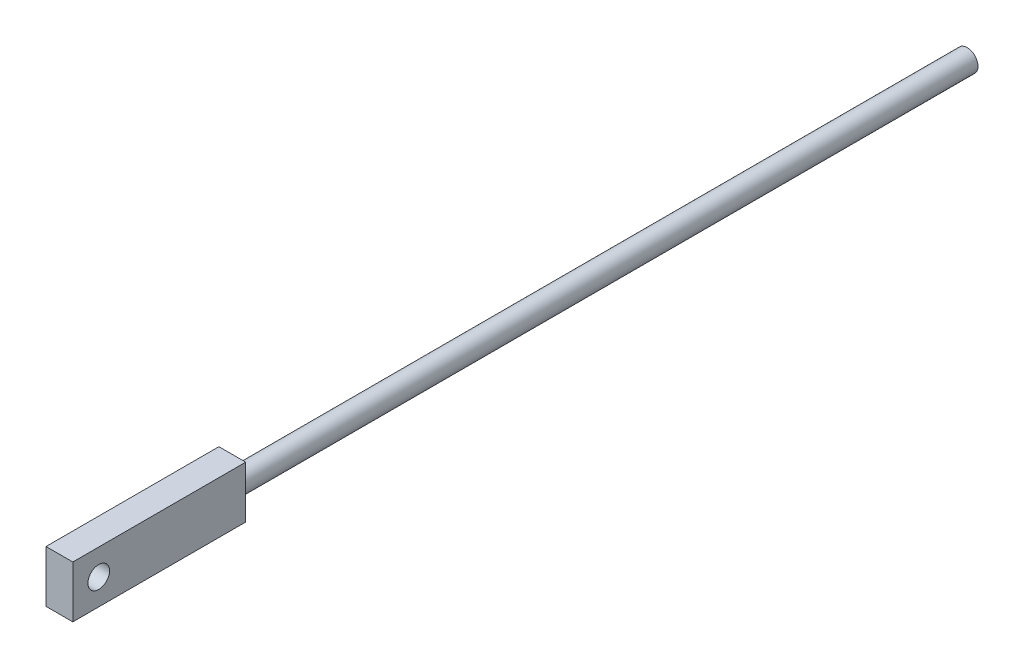
SolidWorks part; units mm, degrees
material "1023 碳钢板 (SS)"
ref_plane "前视基准面" through (0, 0, 0) normal (0, 0, 1) x (1, 0, 0)
ref_plane "上视基准面" through (0, 0, 0) normal (0, 1, 0) x (1, 0, 0)
ref_plane "右视基准面" through (0, 0, 0) normal (1, 0, 0) x (0, 0, -1)
sketch "草图1" plane through (0, 0, 0) normal (0, 0, 1) x (1, 0, 0)
  line L1 (-3.1, -6) -> (3.1, -6)
  line L2 (-3.1, -6) -> (-3.1, 6)
  line L3 (-3.1, 6) -> (3.1, 6)
  line L4 (3.1, -6) -> (3.1, 6)
  line L5 (-3.1, -6) -> (3.1, 6) construction
  line L6 (-3.1, 6) -> (3.1, -6) construction
  point P0 (0, 0)
  dimension "D1" = 6.2
  dimension "D2" = 12
extrude "凸台-拉伸1" add sketch "草图1" along normal blind 40
sketch "草图2" plane through (3.1, 0, 0) normal (1, 0, 0) x (0, 0, -1)
  line L0 (-40, -6) -> (-40, 6) construction
  circle A0 centre (-34, 0) radius 2.5
  dimension "D1" = 5
  dimension "D2" = 6
extrude "切除-拉伸1" cut sketch "草图2" against normal through all
sketch "草图3" plane through (0, 0, 0) normal (0, 0, -1) x (-1, 0, 0)
  circle A0 centre (0, 0) radius 2.5
  dimension "D1" = 5
extrude "凸台-拉伸2" add sketch "草图3" along normal blind 170
